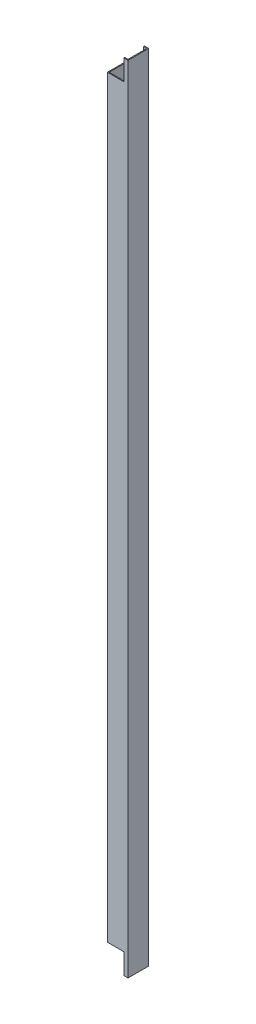
SolidWorks part; units mm, degrees
ref_plane "Front Plane" through (0, 0, 0) normal (0, 0, 1) x (1, 0, 0)
ref_plane "Top Plane" through (0, 0, 0) normal (0, 1, 0) x (1, 0, 0)
ref_plane "Right Plane" through (0, 0, 0) normal (1, 0, 0) x (0, 0, -1)
sketch "Sketch1" plane through (0, 0, 0) normal (0, 1, 0) x (1, 0, 0)
  line L0 (0, 0) -> (0, 50)
  line L1 (0, 50) -> (50, 50)
  line L2 (50, 50) -> (50, 0)
  line L3 (50, 0) -> (0, 0)
  line L4 (2.2, 47.8) -> (47.8, 47.8)
  line L5 (47.8, 47.8) -> (47.8, 2.2)
  line L6 (47.8, 2.2) -> (2.2, 2.2)
  line L7 (2.2, 2.2) -> (2.2, 47.8)
  dimension "D1" = 50
  dimension "D2" = 50
  dimension "D3" = 2.2
extrude "Boss-Extrude1" add sketch "Sketch1" along normal blind 1923
sketch "Sketch2" plane through (0, 0, 0) normal (0, 0, 1) x (1, 0, 0)
  line L0 (0, 0) -> (0, 50)
  line L1 (0, 1923) -> (0, 0) construction
  line L2 (0, 50) -> (40, 50)
  line L3 (40, 50) -> (40, 0)
  line L5 (40, 0) -> (0, 0)
  line L6 (0, 1923) -> (40, 1923)
  line L7 (0, 1923) -> (50, 1923) construction
  line L8 (40, 1923) -> (40, 1873)
  line L9 (40, 1873) -> (0, 1873)
  line L10 (0, 1873) -> (0, 1923)
  dimension "D1" = 50
  dimension "D2" = 40
  dimension "D3" = 50
  dimension "D4" = 40
extrude "Cut-Extrude2" cut sketch "Sketch2" against normal blind 50
equation "\"SquareTube_length\"=1923.0"
equation "\"D1@Boss-Extrude1\"=\"SquareTube_length\""
equation "\"SquareTube_inFront1_cutDepth50_R\"=0.5"
equation "\"D1@Sketch2\" = \"SquareTube_inFront6_cutDepth50_R\""
equation "\"SquareTube_inFront1_cutDepth50_L\"=0.5"
equation "\"D3@Sketch2\"= \"SquareTube_inFront6_cutDepth50_L\""
equation "\"CarBeamWidth\"=700.0"
equation "\"MetalSheet_3mm_length\"=5030.0"
equation "\"MetalSheet_3mm_width\"=1923.0"
equation "\"MetalSheet_3mm_FloorCut_L_length\"=1764.0"
equation "\"MetalSheet_3mm_FloorCut_L_disdance\"=1665.0"
equation "\"MetalSheet_3mm_FloorCut_R_length\"=1764.0"
equation "\"MetalSheet_3mm_FloorCut_R_disdance\"=1665.0"
equation "\"indoorHeight\"=1940.0"
equation "\"x\"=66.0"
equation "\"da\"=62.0"
equation "\"SquareTube_wheel_length\"= 750"
equation "\"channelSteel_length\"=5030.0"
equation "\"SquareTube_inFront2_cutDepth50_R\"=0.5"
equation "\"SquareTube_inFront2_cutDepth50_L\"=0.5"
equation "\"SquareTube_inFront3_cutDepth50_R\"=0.5"
equation "\"SquareTube_inFront3_cutDepth50_L\"=0.5"
equation "\"SquareTube_inFront4_cutDepth50_R\"=0.5"
equation "\"SquareTube_inFront4_cutDepth50_L\"=0.5"
equation "\"SquareTube_inFront5_cutDepth50_R\"=50"
equation "\"SquareTube_inFront5_cutDepth50_L\"=50"
equation "\"SquareTube_inFront6_cutDepth50_R\"=50"
equation "\"SquareTube_inFront6_cutDepth50_L\"=50"
equation "\"SquareTube_inFront7_cutDepth50_R\"=50"
equation "\"SquareTube_inFront7_cutDepth50_L\"=50"
equation "\"SquareTube_inFront8_cutDepth50_R\"=50"
equation "\"SquareTube_inFront8_cutDepth50_L\"=50"
equation "\"SquareTube_inFront9_cutDepth50_R\"=50"
equation "\"SquareTube_inFront9_cutDepth50_L\"=50"
equation "\"SquareTube_inFront10_cutDepth50_R\"=50"
equation "\"SquareTube_inFront10_cutDepth50_L\"=50"
equation "\"SquareTube_inBack1_cutDepth50_R\"=50"
equation "\"SquareTube_inBack1_cutDepth50_L\"=50"
equation "\"SquareTube_inBack2_cutDepth50_R\"=50"
equation "\"SquareTube_inBack2_cutDepth50_L\"=50"
equation "\"SquareTube_inBack3_cutDepth50_R\"=50"
equation "\"SquareTube_inBack3_cutDepth50_L\"=50"
equation "\"SquareTube_inBack4_cutDepth50_R\"=50"
equation "\"SquareTube_inBack4_cutDepth50_L\"=50"
equation "\"SquareTube_inBack5_cutDepth50_R\"=50"
equation "\"SquareTube_inBack5_cutDepth50_L\"=50"
equation "\"SquareTube_inBack6_cutDepth50_R\"=0.5"
equation "\"SquareTube_inBack6_cutDepth50_L\"=0.5"
